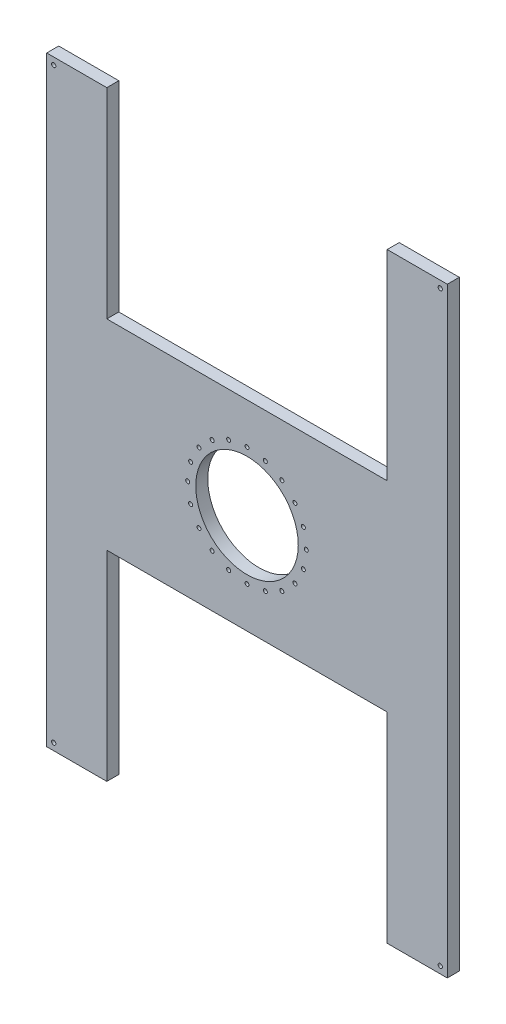
SolidWorks part; units mm, degrees
material "ASTM A36 Acier"
ref_plane "Plan de face" through (0, 0, 0) normal (0, 0, 1) x (1, 0, 0)
ref_plane "Plan de dessus" through (0, 0, 0) normal (0, 1, 0) x (1, 0, 0)
ref_plane "Plan de droite" through (0, 0, 0) normal (1, 0, 0) x (0, 0, -1)
sketch "Esquisse1" plane through (0, 0, 0) normal (0, 0, 1) x (1, 0, 0)
  line L0 (-1000, 2000) -> (-700, 2000)
  line L1 (-700, 2000) -> (-700, 1000)
  line L2 (-700, 1000) -> (700, 1000)
  line L3 (700, 1000) -> (700, 2000)
  line L4 (700, 2000) -> (1000, 2000)
  line L5 (1000, 2000) -> (1000, -1000)
  line L6 (1000, -1000) -> (700, -1000)
  line L7 (700, -1000) -> (700, 0)
  line L8 (700, 0) -> (-700, 0)
  line L9 (-700, 0) -> (-700, -1000)
  line L10 (-700, -1000) -> (-1000, -1000)
  line L11 (-1000, -1000) -> (-1000, 2000)
  point P15 (0, 0)
  dimension "D1" = 2000
  dimension "D2" = 3000
  dimension "D3" = 3000
  dimension "D4" = 300
  dimension "D5" = 300
  dimension "D6" = 300
  dimension "D7" = 300
  dimension "D8" = 1000
  dimension "D9" = 1000
  dimension "D10" = 1400
extrude "Boss.-Extru.1" add sketch "Esquisse1" along normal blind 60
sketch "Esquisse2" plane through (0, 0, 60) normal (0, 0, 1) x (1, 0, 0)
  circle A0 centre (0, 500) radius 256
  dimension "D1" = 512
  dimension "D2" = 500
extrude "Enlèv. mat.-Extru.1" cut sketch "Esquisse2" against normal through all
sketch "Esquisse4" plane through (0, 0, 0) normal (1, 0, 0) x (0, 0, -1)
  line L0 (0, 500) -> (1429.3387, 500) construction
  dimension "D1" = 500
sketch "Esquisse5" plane through (0, 0, 0) normal (0, 0, 1) x (1, 0, 0)
  circle A0 centre (0, 796) radius 10
  dimension "D1" = 20
  dimension "D2" = 296
extrude "Enlèv. mat.-Extru.3" cut sketch "Esquisse5" along normal through all
pattern_circular "Répétition circulaire1" count 20 every 18 about axis through (0, 500, 0) along (0, 0, 1) of "Enlèv. mat.-Extru.3"
ref_plane "Plan1" through (0, 0, 0) normal (0, 0, -1) x (-1, 0, 0)
sketch "Esquisse6" plane through (0, 0, 0) normal (0, 0, -1) x (-1, 0, 0)
  line L0 (-1000, 2000) -> (-700, 2000) construction
  line L1 (-1000, -1000) -> (-1000, 2000) construction
  line L2 (700, 2000) -> (1000, 2000) construction
  line L3 (1000, 2000) -> (1000, -1000) construction
  line L4 (1000, -1000) -> (700, -1000) construction
  line L5 (-700, -1000) -> (-1000, -1000) construction
  circle A0 centre (-965, 1965) radius 10.5
  circle A1 centre (-965, -965) radius 10.5
  circle A2 centre (965, -965) radius 10.5
  circle A3 centre (965, 1965) radius 10.5
  dimension "D1" = 35
  dimension "D2" = 21
  dimension "D3" = 21
  dimension "D6" = 21
  dimension "D9" = 35
  dimension "21" = 21
  dimension "35" = 35
  dimension "D4" = 35
  dimension "D5" = 35
  dimension "D7" = 35
  dimension "D8" = 35
  dimension "D10" = 35
extrude "Enlèv. mat.-Extru.4" cut sketch "Esquisse6" against normal through all
